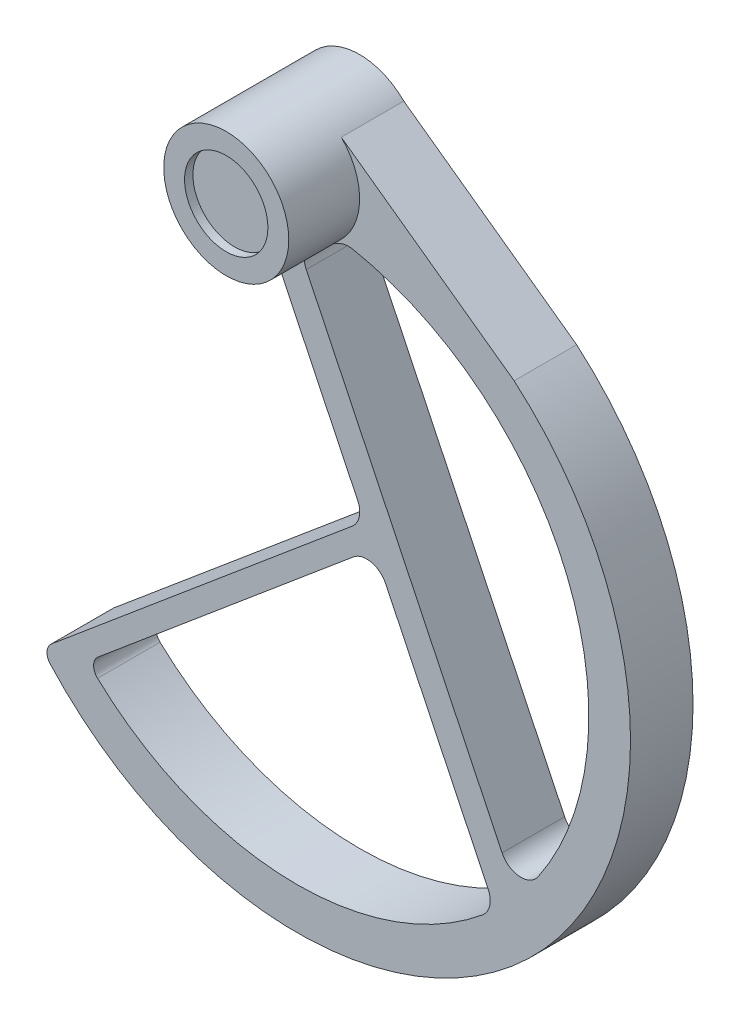
SolidWorks part; units mm, degrees
ref_plane "正面" through (0, 0, 0) normal (0, 0, 1) x (1, 0, 0)
ref_plane "平面" through (0, 0, 0) normal (0, 1, 0) x (1, 0, 0)
ref_plane "右側面" through (0, 0, 0) normal (1, 0, 0) x (0, 0, -1)
sketch "ｽｹｯﾁ4" plane through (0, 0, 0) normal (0, 0, 1) x (1, 0, 0)
  line L0 (0, 0.7897) -> (0, 0)
  line L1 (-53.6231, -124.9951) -> (-58.9406, -129.4571)
  line L3 (-10.6066, -10.6066) -> (14.5363, -62.8896)
  line L4 (-53.6231, -124.9951) -> (13.2442, -68.8868)
  line L5 (21.2324, -76.8138) -> (45.8448, -127.9938)
  line L6 (10.6066, 10.6066) -> (52.0762, -19.2705)
  line L7 (-58.0696, -135.2532) -> (-57.9498, -135.1527)
  line L8 (-47.7477, -126.5866) -> (13.5112, -75.1515)
  arc A1 (-59.2335, -133.7716) -> (52.0762, -19.2705) centre (0, -80) ccw
  arc A2 (-47.8702, -131.073) -> (44.5187, -134.0193) centre (0, -80) ccw
  arc A3 (10.6066, 10.6066) -> (-10.6066, -10.6066) centre (0, 0) ccw
  arc A4 (-59.2335, -133.7716) -> (-58.9406, -129.4571) centre (-57.0123, -131.7552) cw
  arc A5 (-47.8702, -131.073) -> (-47.7477, -126.5866) centre (-45.8186, -128.8841) cw
  arc A6 (13.5112, -75.1515) -> (21.2324, -76.8138) centre (16.7264, -78.9807) cw
  arc A7 (13.2442, -68.8868) -> (14.5363, -62.8896) centre (10.0302, -65.0566) ccw
  arc A8 (45.8448, -127.9938) -> (44.5187, -134.0193) centre (41.3388, -130.1608) cw
  point P18 (-61.2836, -131.423)
  point P21 (-50.2744, -128.7081)
  point P24 (18.4421, -71.0114)
  dimension "D3" = 140
  dimension "D4" = 30
  dimension "D5" = 5
  dimension "D6" = 3
  dimension "D7" = 3
  dimension "D8" = 5
  dimension "D9" = 5
  dimension "D10" = 5
  dimension "D2" = 5
extrude "ﾎﾞｽ - 押し出し1" add sketch "ｽｹｯﾁ4" along normal blind 15
sketch "ｽｹｯﾁ6" plane through (0, 0, 15) normal (0, 0, 1) x (1, 0, 0)
  line L6 (49.1896, -118.7973) -> (2.2018, -21.089)
  line L7 (6.4834, -13.4819) -> (4.5408, -14.416)
  line L8 (6.4834, -13.4819) -> (10.2197, -11.6851)
  arc A0 (57.8261, -119.448) -> (13.3394, -11.2828) centre (0, -80) ccw
  arc A1 (2.2018, -21.089) -> (4.5408, -14.416) centre (6.7078, -18.9221) cw
  arc A2 (13.3394, -11.2828) -> (10.2197, -11.6851) centre (12.3866, -16.1911) ccw
  arc A3 (57.8261, -119.448) -> (49.1896, -118.7973) centre (53.6956, -116.6303) cw
  point P7 (0.0348, -16.583)
  point P14 (52.6925, -126.0814)
  dimension "D3" = 121.502
  dimension "D4" = 70
  dimension "D1" = 5
  dimension "D2" = 5
  dimension "D5" = 5
  dimension "D6" = 90
extrude "ｶｯﾄ - 押し出し1" cut sketch "ｽｹｯﾁ6" against normal blind 15
sketch "ｽｹｯﾁ9" plane through (0, 0, 15) normal (0, 0, 1) x (1, 0, 0)
  circle A0 centre (0, 0) radius 15
extrude "ﾎﾞｽ - 押し出し2" add sketch "ｽｹｯﾁ9" along normal blind 17
sketch "ｽｹｯﾁ10" plane through (0, 0, 32) normal (0, 0, 1) x (1, 0, 0)
  circle A0 centre (0, 0) radius 10
extrude "ｶｯﾄ - 押し出し4" cut sketch "ｽｹｯﾁ10" against normal blind 2
